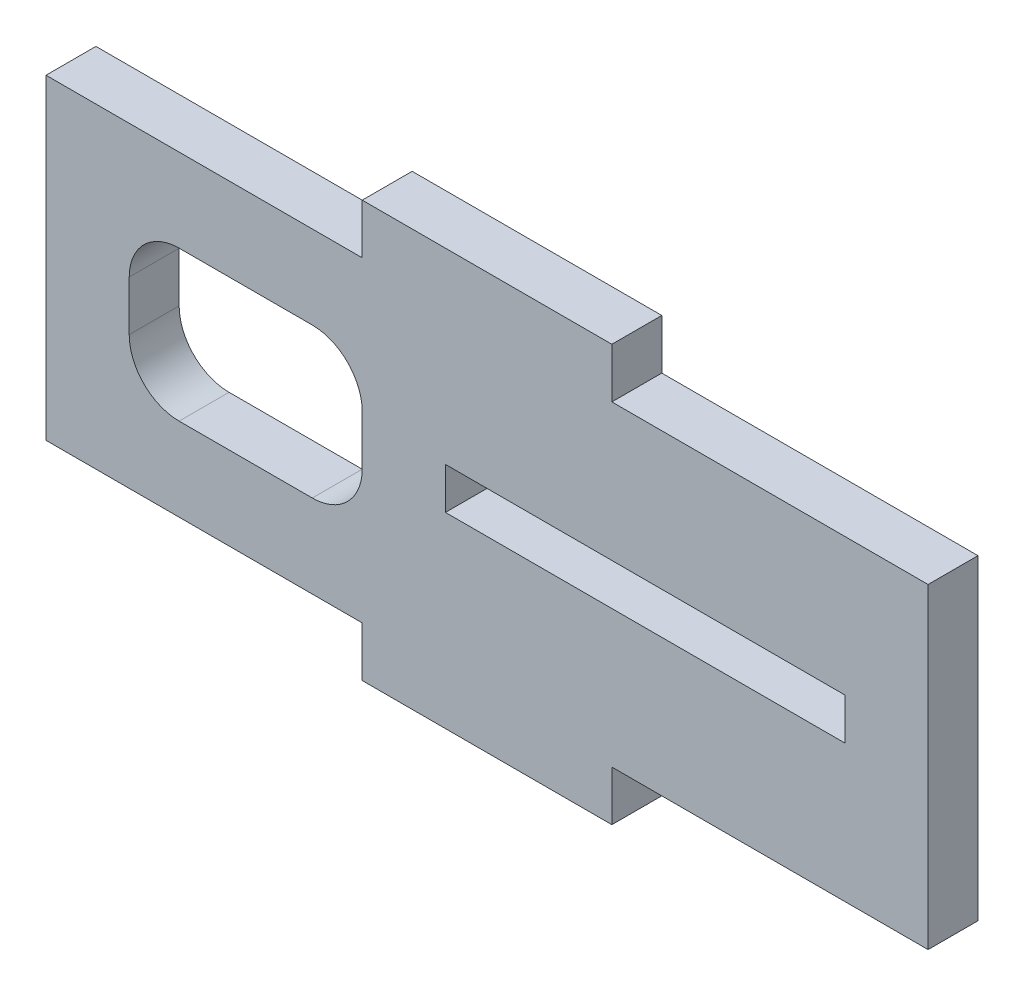
SolidWorks part; units mm, degrees
material "ABS PC"
ref_plane "Front Plane" through (0, 0, 0) normal (0, 0, 1) x (1, 0, 0)
ref_plane "Top Plane" through (0, 0, 0) normal (0, 1, 0) x (1, 0, 0)
ref_plane "Right Plane" through (0, 0, 0) normal (1, 0, 0) x (0, 0, -1)
sketch "Sketch1" plane through (0, 0, 0) normal (0, 0, 1) x (1, 0, 0)
  line L0 (0, 12.5) -> (0, 0) construction
  line L1 (-2.5, 1.25) -> (21.5, 1.25)
  line L2 (-2.5, 1.25) -> (-2.5, -1.25)
  line L3 (-2.5, -1.25) -> (21.5, -1.25)
  line L4 (21.5, 1.25) -> (21.5, -1.25)
  line L5 (0, 0) -> (0, -12.5) construction
  line L6 (-26.5, -9.5) -> (-26.5, 9.5)
  line L7 (-26.5, 9.5) -> (-7.5, 9.5)
  line L8 (26.5, 9.5) -> (26.5, -9.5)
  line L9 (26.5, -9.5) -> (7.5, -9.5)
  line L10 (7.5, -9.5) -> (7.5, -12.5)
  line L11 (7.5, -12.5) -> (-7.5, -12.5)
  line L12 (-7.5, -12.5) -> (-7.5, -9.5)
  line L13 (-7.5, -9.5) -> (-26.5, -9.5)
  line L14 (9.5, 9.5) -> (9.5, 1.25) construction
  line L15 (9.5, 1.25) -> (9.5, -1.25) construction
  line L16 (-7.5, 9.5) -> (-7.5, 12.5)
  line L17 (-7.5, 12.5) -> (7.5, 12.5)
  line L18 (7.5, 12.5) -> (7.5, 9.5)
  line L19 (7.5, 9.5) -> (26.5, 9.5)
  line L20 (9.5, -1.25) -> (9.5, -9.5) construction
  line L22 (-18.5, 4.5) -> (-10.5, 4.5)
  line L23 (-21.5, 1.5) -> (-21.5, -1.5)
  line L24 (-18.5, -4.5) -> (-10.5, -4.5)
  line L25 (-7.5, 1.5) -> (-7.5, -1.5)
  arc A0 (-10.5, 4.5) -> (-7.5, 1.5) centre (-10.5, 1.5) cw
  arc A1 (-7.5, -1.5) -> (-10.5, -4.5) centre (-10.5, -1.5) cw
  arc A2 (-18.5, -4.5) -> (-21.5, -1.5) centre (-18.5, -1.5) cw
  arc A3 (-21.5, 1.5) -> (-18.5, 4.5) centre (-18.5, 1.5) cw
  dimension "D8" = 3
  dimension "D1" = 24
  dimension "D2" = 2.5
  dimension "D3" = 3
  dimension "D4" = 5
  dimension "D5" = 19
  dimension "D6" = 53
  dimension "D7" = 15
  dimension "D9" = 5
  dimension "D10" = 5
  dimension "D11" = 5
  dimension "D12" = 5
extrude "Boss-Extrude1" add sketch "Sketch1" along normal blind 3
fillet "Fillet1" [suppressed] radius 3
ref_plane "Plane1" through (9.5, 0, 0) normal (1, 0, 0) x (0, 0, -1)
